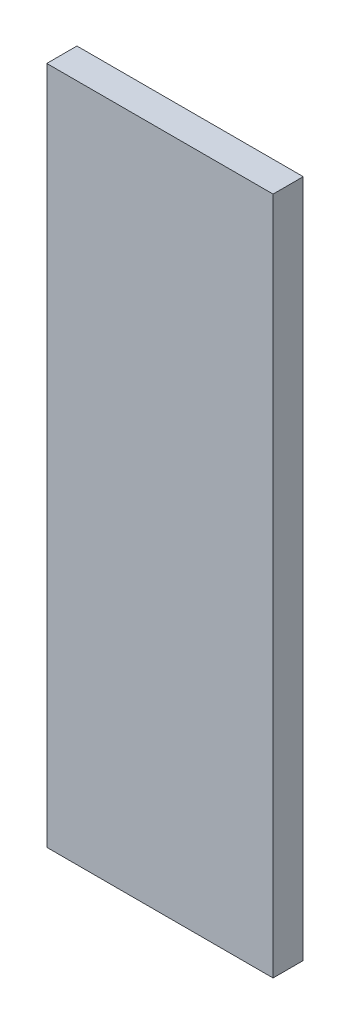
SolidWorks part; units mm, degrees
material "AISI 304"
ref_plane "Płaszczyzna przednia" through (0, 0, 0) normal (0, 0, 1) x (1, 0, 0)
ref_plane "Płaszczyzna górna" through (0, 0, 0) normal (0, 1, 0) x (1, 0, 0)
ref_plane "Płaszczyzna prawa" through (0, 0, 0) normal (1, 0, 0) x (0, 0, -1)
sketch "Szkic1" plane through (0, 0, 0) normal (0, 0, 1) x (1, 0, 0)
  line L1 (0, 0) -> (15, 0)
  line L2 (0, 0) -> (0, 45)
  line L3 (0, 45) -> (15, 45)
  line L4 (15, 0) -> (15, 45)
  dimension "D1" = 45
  dimension "D2" = 15
extrude "Dodanie-wyciągnięcie1" add sketch "Szkic1" along normal blind 2
